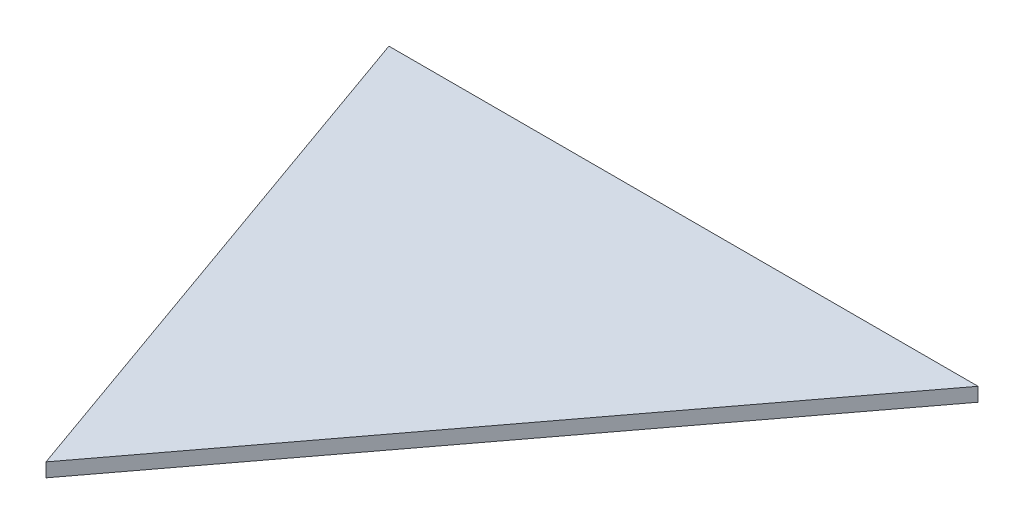
SolidWorks part; units mm, degrees
ref_plane "Front Plane" through (0, 0, 0) normal (0, 0, 1) x (1, 0, 0)
ref_plane "Top Plane" through (0, 0, 0) normal (0, 1, 0) x (1, 0, 0)
ref_plane "Right Plane" through (0, 0, 0) normal (1, 0, 0) x (0, 0, -1)
sketch "Sketch2" plane through (0, 0, 0) normal (0, 1, 0) x (1, 0, 0)
  line L0 (-57.15, 0) -> (224.536, 0)
  line L1 (224.536, 0) -> (-24.3577, -196.7539)
  line L2 (-24.3577, -196.7539) -> (-57.15, 0)
  line L3 (0, 0) -> (0, -152.4) construction
  line L4 (-31.75, -152.4) -> (31.75, -152.4) construction
  point P2 (0, 0)
  dimension "D1" = 281.686
  dimension "D2" = 57.15
  dimension "D3" = 63.5
  dimension "D4" = 152.4
extrude "Boss-Extrude1" add sketch "Sketch2" along normal blind 152.4
ref_plane "Plane1" through (-63.5, 0, 0) normal (1, 0, 0) x (0, 0, -1)
sketch "Sketch3" plane through (-63.5, 0, 0) normal (1, 0, 0) x (0, 0, -1)
  line L0 (0, 76.2) -> (-152.4, 76.2) construction
  line L1 (0, 152.4) -> (0, 0) construction
  line L2 (-152.4, 44.45) -> (-152.4, 107.95) construction
  line L3 (0, 152.4) -> (-152.4, 107.95)
  line L4 (0, 0) -> (-152.4, 44.45)
  line L5 (-152.4, 107.95) -> (-261.2571, 76.2)
  line L6 (-152.4, 44.45) -> (-261.2571, 76.2)
  line L7 (0, 152.4) -> (0, 0)
  point P7 (-152.4, 76.2)
  dimension "D1" = 152.4
  dimension "D2" = 63.5
extrude "Cut-Extrude2" cut sketch "Sketch3" along normal through all flip side to cut
shell "Shell1" thickness 6.35
ref_plane "Plane2" through (0, -12.7, 0) normal (0, 1, 0) x (1, 0, 0)
sketch "Sketch4" plane through (-63.5, 0, 0) normal (1, 0, 0) x (0, 0, -1)
  line L0 (0, 152.4) -> (0, 145.7854) construction
  line L1 (0, 145.7854) -> (-196.7539, 88.3989)
  line L2 (-196.7539, 95.0134) -> (-196.7539, 57.3866) construction
  line L3 (-196.7539, 88.3989) -> (-196.7539, 95.0134) construction
  line L4 (-196.7539, 95.0134) -> (0, 152.4) construction
  line L5 (-196.7539, 57.3866) -> (0, 0) construction
  line L7 (0, -70.5856) -> (-196.7539, -13.1991)
  line L8 (-196.7539, -13.1991) -> (-196.7539, 57.3866) construction
  line L9 (0, 145.7854) -> (0, -70.5856)
  line L10 (-196.7539, -13.1991) -> (-196.7539, 88.3989)
extrude "Cut-Extrude3" cut sketch "Sketch4" along normal through all
